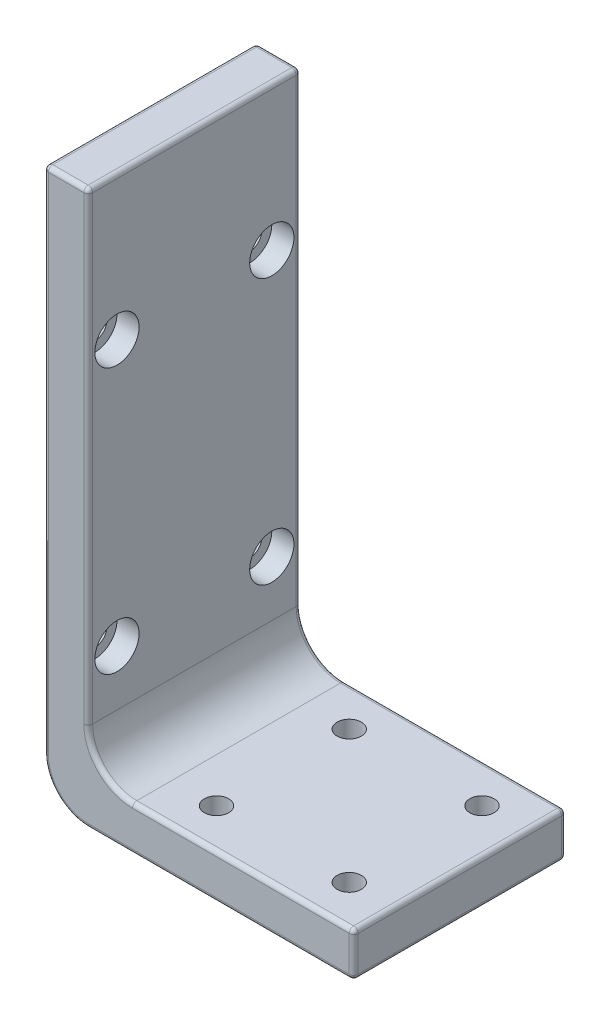
SolidWorks part; units mm, degrees
material "Nylon 101"
ref_plane "Front Plane" through (0, 0, 0) normal (0, 0, 1) x (1, 0, 0)
ref_plane "Top Plane" through (0, 0, 0) normal (0, 1, 0) x (1, 0, 0)
ref_plane "Right Plane" through (0, 0, 0) normal (1, 0, 0) x (0, 0, -1)
sketch "Sketch1" plane through (0, 0, 0) normal (0, 0, 1) x (1, 0, 0)
  line L0 (0, 125) -> (0, 0)
  line L1 (0, 0) -> (70, 0)
  line L2 (70, 0) -> (70, 10)
  line L3 (70, 10) -> (10, 10)
  line L4 (10, 10) -> (10, 125)
  line L5 (10, 125) -> (0, 125)
  dimension "D1" = 60
  dimension "D2" = 10
  dimension "D3" = 10
  dimension "D4" = 125
extrude "base" add sketch "Sketch1" along normal blind 48
fillet "root_edge_fillet" radius 10 2 edges at (0, 0, 24) (10, 10, 24)
hole_wizard "slider_bolt_hole_pattern" positions "Sketch2" profile "Sketch3" counterbore size "M5" standard "ANSI Metric" end condition through all
sketch "Sketch2" plane through (10, 0, 0) normal (1, 0, 0) x (0, 0, -1)
  line L2 (-41.5, 92.5) -> (-6.5, 92.5)
  line L3 (-41.5, 92.5) -> (-41.5, 32.5)
  line L4 (-41.5, 32.5) -> (-6.5, 32.5)
  line L5 (-6.5, 92.5) -> (-6.5, 32.5)
  line L6 (-24, 92.5) -> (-24, 125)
  line L7 (-48, 125) -> (0, 125) construction
  line L11 (-24, 32.5) -> (-24, 0)
  line L12 (-48, 0) -> (0, 0) construction
  point P58 (-41.5, 92.5)
  point P59 (-6.5, 32.5)
  point P108 (-41.5, 32.5)
  point P109 (-6.5, 92.5)
  dimension "D1" = 35
  dimension "D2" = 60
sketch "Sketch3" plane through (10, 92.5, 41.5) normal (0, 1, 0) x (0, 0, -1)
  line L0 (0, 0) -> (0, 10)
  line L1 (0, 10) -> (2.75, 10)
  line L3 (2.75, 10) -> (2.75, 5)
  line L4 (2.75, 5) -> (5, 5)
  line L5 (5, 5) -> (5, 0)
  line L7 (5, 0) -> (0, 0)
  line L11 (0, -6.35) -> (0, 107.95) construction
  dimension "Thru Hole Dia." = 5.5
  dimension "Thru Hole Depth" = 10
  dimension "C'Bore Dia." = 10
  dimension "C'Bore Depth" = 5
hole_wizard "desktop_bolt_hole_pattern" positions "Sketch4" profile "Sketch5" hole size "M5" standard "ANSI Metric" end condition through all
sketch "Sketch4" plane through (0, 10, 0) normal (0, 1, 0) x (1, 0, 0)
  line L1 (30, -9) -> (60, -9)
  line L2 (30, -9) -> (30, -39)
  line L3 (30, -39) -> (60, -39)
  line L4 (60, -9) -> (60, -39)
  line L5 (45, -9) -> (45, 0)
  line L6 (70, 0) -> (20, 0) construction
  line L8 (60, -24) -> (70, -24)
  line L9 (70, -48) -> (70, 0) construction
  point P1 (30, -9)
  point P2 (60, -39)
  point P63 (30, -39)
  point P64 (60, -9)
  dimension "D1" = 30
  dimension "D2" = 30
sketch "Sketch5" plane through (30, 10, 9) normal (1, 0, 0) x (0, 0, 1)
  line L0 (0, 0) -> (0, 10)
  line L1 (0, 10) -> (2.75, 10)
  line L2 (2.75, 10) -> (2.75, 0)
  line L5 (2.75, 0) -> (0, 0)
  line L11 (0, -6.35) -> (0, 107.95) construction
  dimension "Thru Hole Dia." = 5.5
  dimension "Thru Hole Depth" = 10
fillet "external_fillet" radius 1 20 edges at (10, 125, 24) (0, 125, 24) (70, 0, 24) (70, 10, 24) (70, 5, 0) (45, 10, 0) (12.9289, 12.9289, 0) (10, 72.5, 0) (5, 125, 0) (0, 67.5, 0) (2.9289, 2.9289, 0) (40, 0, 0) (5, 125, 48) (10, 72.5, 48) (12.9289, 12.9289, 48) (45, 10, 48) (70, 5, 48) (40, 0, 48) (2.9289, 2.9289, 48) (0, 67.5, 48)
equation "\"board_thickness\" = 12mm"
equation "\"way_width\"= 75mm"
equation "\"way_thickness\"= 50mm"
equation "\"radial_clearance\"= 0.1mm"
equation "\"slider_width\"= \"way_width\"-2* \"radial_clearance\""
equation "\"slider_thickness\" = \"way_thickness\" - 2 * \"radial_clearance\""
equation "\"column_width\"= \"way_width\" + 2 * \"board_thickness\""
equation "\"boxway_slot_width\" = 50mm"
equation "\"keeper_rail_width\" = (\"column_width\" - \"boxway_slot_width\")/2"
equation "\"slider_length\" = 125mm"
equation "\"nut_diameter\"= 22mm"
equation "\"nut_length\"= 15mm"
equation "\"leadscrew_diameter\"= 10mm"
equation "\"leadscrew_radial_clearance\"= 1mm"
equation "\"bearing_bolt_pattern_height\" = 60mm"
equation "\"bearing_bolt_pattern_width\" = 35mm"
equation "\"D1@Sketch2\"=\"bearing_bolt_pattern_width\""
equation "\"D2@Sketch2\"=\"bearing_bolt_pattern_height\""
equation "\"desktop_bolt_pattern_width\" = 30mm"
equation "\"desktop_bolt_pattern_height\" = 30mm"
equation "\"D1@Sketch4\"=\"desktop_bolt_pattern_height\""
equation "\"D2@Sketch4\"=\"desktop_bolt_pattern_width\""
equation "\"D4@Sketch1\"=\"slider_length\""
equation "\"D1@base\"=\"boxway_slot_width\" - 2mm"
